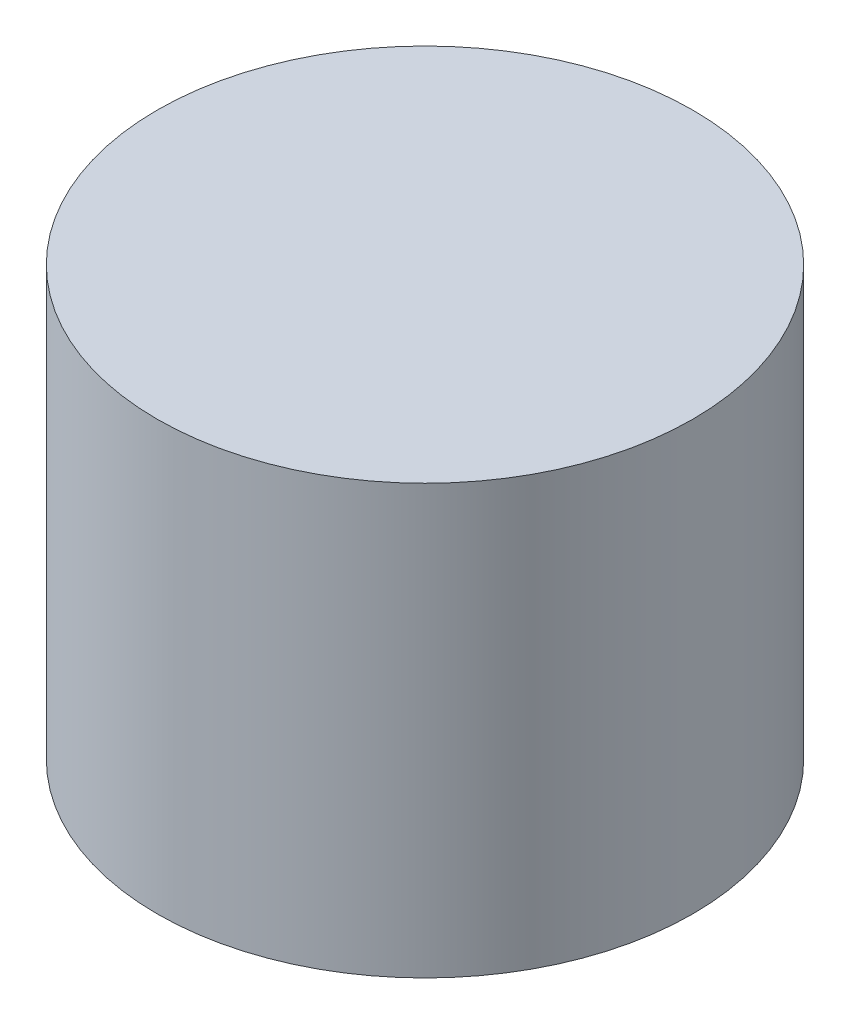
SolidWorks part; units mm, degrees
material "2024 Alloy"
ref_plane "Front Plane" through (0, 0, 0) normal (0, 0, 1) x (1, 0, 0)
ref_plane "Top Plane" through (0, 0, 0) normal (0, 1, 0) x (1, 0, 0)
ref_plane "Right Plane" through (0, 0, 0) normal (1, 0, 0) x (0, 0, -1)
sketch "Sketch1" plane through (0, 0, 0) normal (0, 1, 0) x (1, 0, 0)
  circle A0 centre (0, 0) radius 6.25
  dimension "D1" = 12.5
extrude "Boss-Extrude1" add sketch "Sketch1" along normal blind 10
